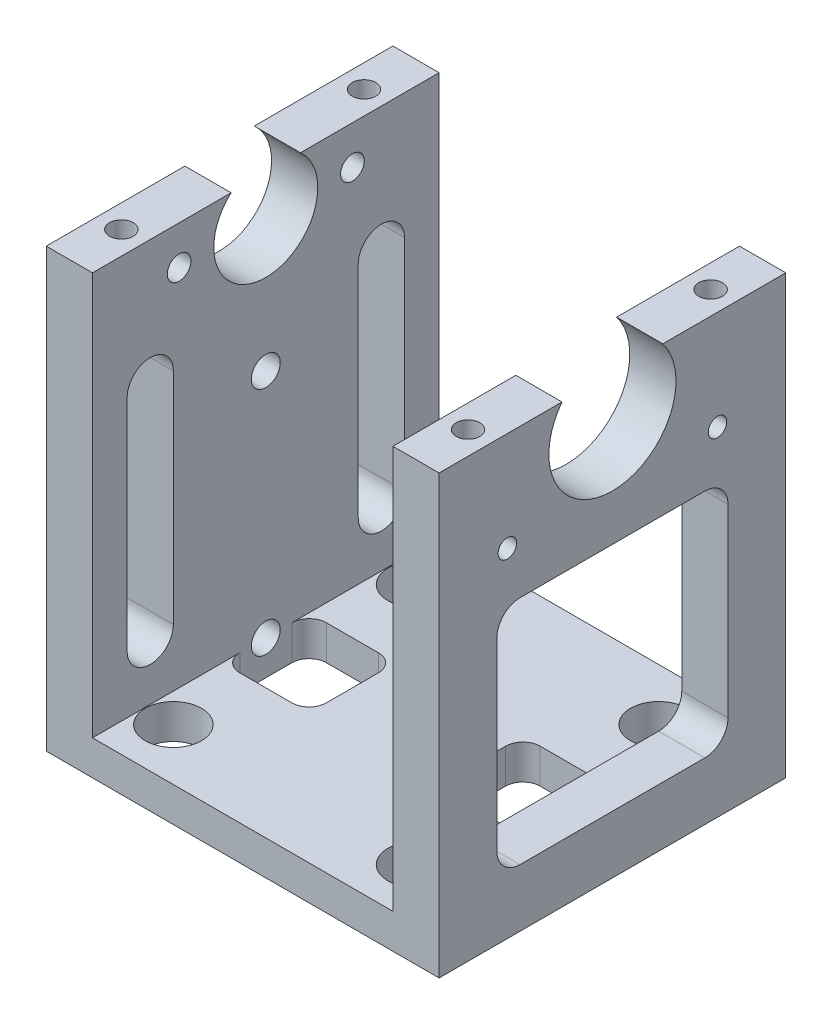
SolidWorks part; units mm, degrees
material "6061 合金"
ref_plane "前视基准面" through (0, 0, 0) normal (0, 0, 1) x (1, 0, 0)
ref_plane "上视基准面" through (0, 0, 0) normal (0, 1, 0) x (1, 0, 0)
ref_plane "右视基准面" through (0, 0, 0) normal (1, 0, 0) x (0, 0, -1)
sketch "草图1" plane through (0, 0, 0) normal (0, 0, 1) x (1, 0, 0)
  line L0 (0, 0) -> (34, 0)
  line L1 (34, 0) -> (34, 44.5)
  line L2 (0, 0) -> (0, 42)
  line L3 (30, 4) -> (30, 44.5)
  line L5 (4, 4) -> (4, 42)
  line L6 (0, 42) -> (4, 42)
  line L7 (30, 44.5) -> (34, 44.5)
  line L8 (30, 4) -> (30, 3)
  line L9 (30, 3) -> (4, 3)
  line L10 (4, 3) -> (4, 4)
  line L12 (4, 4) -> (30, 4) construction
  dimension "D1" = 34
  dimension "D2" = 44.5
  dimension "D3" = 42
  dimension "D4" = 4
  dimension "D5" = 1
extrude "凸台-拉伸1" add sketch "草图1" along normal mid plane 30
chamfer "倒角1" distance 10 angle 45 4 edges at (32, 44.5, -15) (32, 44.5, 15) (2, 42, -15) (2, 42, 15)
sketch "草图2" plane through (34, 0, 0) normal (1, 0, 0) x (0, 0, -1)
  line L0 (-5, 44.5) -> (5, 44.5) construction
  circle A0 centre (0, 34.5) radius 4.5
  dimension "D1" = 9
  dimension "D2" = 10
extrude "切除-拉伸1" cut sketch "草图2" against normal through all
sketch "草图3" plane through (34, 0, 0) normal (1, 0, 0) x (0, 0, -1)
  line L0 (-5, 44.5) -> (5, 44.5) construction
  line L1 (-10, 25) -> (10, 25)
  line L2 (-10, 25) -> (-10, 5)
  line L3 (-10, 5) -> (10, 5)
  line L4 (10, 25) -> (10, 5)
  line L5 (-10, 25) -> (10, 5) construction
  line L6 (-10, 5) -> (10, 25) construction
  point P0 (0, 15)
  dimension "D1" = 20
  dimension "D2" = 19.5
  dimension "D3" = 20
extrude "切除-拉伸2" cut sketch "草图3" against normal blind 10
fillet "圆角1" radius 2 4 edges at (32, 25, 10) (32, 25, -10) (32, 5, -10) (32, 5, 10)
sketch "草图4" plane through (0, 0, 0) normal (-1, 0, 0) x (0, 0, 1)
  line L0 (0, 0) -> (0, 42) construction
  line L1 (5, 42) -> (-5, 42) construction
  line L2 (15, 0) -> (-15, 0) construction
  line L3 (-4.5, 28) -> (4.5, 28)
  line L4 (-4.5, 28) -> (-4.5, 0)
  line L5 (-4.5, 0) -> (4.5, 0)
  line L6 (4.5, 28) -> (4.5, 0)
  dimension "D1" = 9
  dimension "D2" = 4.5
  dimension "D3" = 28
extrude "切除-拉伸3" cut sketch "草图4" against normal blind 1
fillet "圆角2" radius 2 2 edges at (0.5, 28, -4.5) (0.5, 28, 4.5)
sketch "草图5" plane through (34, 0, 0) normal (1, 0, 0) x (0, 0, -1)
  line L0 (-15, 34.5) -> (15, 34.5) construction
  line L1 (0, 44.5) -> (0, 29.6692) construction
  line L2 (-5, 44.5) -> (5, 44.5) construction
  line L3 (-3, 44.5) -> (-3, 29.6692) construction
  line L4 (3, 44.5) -> (3, 29.6692) construction
  line L5 (-3, 37.8541) -> (-15, 37.8541)
  line L6 (-3, 37.8541) -> (15, 37.8541)
  line L7 (15, 37.8541) -> (15, 44.5)
  line L8 (15, 44.5) -> (-15, 44.5)
  line L9 (-15, 44.5) -> (-15, 37.8541)
  circle A0 centre (0, 34.5) radius 4.5 construction
  point P0 (0, 45)
  point P17 (0, 34.5)
  point P21 (9.0933, 29.25)
  point P22 (-9.0933, 29.25)
  point P23 (0, 34.5)
  dimension "D1" = 10.5
  dimension "D2" = 3
  dimension "D3" = 3
hole_wizard "M2 螺纹孔2" positions "3D草图2" profile "草图7" tap size "M2" standard "GB"
sketch3d "3D草图2"
  point P0 (34, 29.25, 9.0933)
  point P3 (34, 29.25, -9.0933)
sketch "草图7" plane through (34, 29.25, 9.0933) normal (0, 1, 0) x (0, 0, -1)
  line L0 (0, 0) -> (0, 6.4807)
  line L1 (0, 6.4807) -> (0.8, 6)
  line L2 (0.8, 6) -> (0.8, 0)
  line L5 (0.8, 0) -> (0, 0)
  line L10 (0, 6.4807) -> (-0.8, 6) construction
  line L11 (0, -6.35) -> (0, 107.95) construction
  dimension "螺纹孔钻头直径" = 1.6
  dimension "螺纹孔钻头深度" = 6
  dimension "导头角度" = 118
cosmetic thread "孔螺蚊线2" parameters "D1"=4, "D2"=2
cosmetic thread "孔螺蚊线3" parameters "D1"=4, "D2"=2
extrude "切除-拉伸4" cut sketch "草图5" against normal through all
sketch "草图9" plane through (0, 0, 0) normal (-1, 0, 0) x (0, 0, 1)
  line L0 (15, 32) -> (15, 37.8541)
  line L1 (15, 37.8541) -> (9.1459, 37.8541)
  line L2 (9.1459, 37.8541) -> (15, 32)
  line L3 (-15, 32) -> (-15, 37.8541)
  line L4 (-15, 37.8541) -> (-9.1459, 37.8541)
  line M1 (15, 32) -> (9.1459, 37.8541)
  line M5 (-9.1459, 37.8541) -> (-15, 32)
extrude "凸台-拉伸2" add sketch "草图9" against normal blind 4 contours L0 L1 M1 | L4 L3 M5
sketch "草图10" plane through (34, 0, 0) normal (1, 0, 0) x (0, 0, -1)
  line L0 (11.6459, 37.8541) -> (15, 37.8541)
  line L1 (15, 37.8541) -> (3, 37.8541) construction
  line L2 (15, 3) -> (15, 37.8541) construction
  line L3 (15, 37.8541) -> (15, 34.5)
  line L4 (15, 34.5) -> (11.6459, 37.8541)
  line L5 (-15, 34.5) -> (-15, 37.8541)
  line L6 (-15, 37.8541) -> (-11.6459, 37.8541)
  line L7 (-11.6459, 37.8541) -> (-15, 34.5)
extrude "凸台-拉伸3" add sketch "草图10" against normal blind 4
sketch "草图11" plane through (0, 0, 0) normal (-1, 0, 0) x (0, 0, 1)
  line L0 (-10, 27) -> (-10, 8) construction
  line L1 (-4.5, 0) -> (-15, 0) construction
  line L2 (-8, 27) -> (-8, 8)
  line L3 (-12, 27) -> (-12, 8)
  line L5 (0, 0) -> (0, 37.2192) construction
  line L6 (10, 27) -> (10, 8) construction
  line L7 (8, 27) -> (8, 8)
  line L8 (12, 27) -> (12, 8)
  arc A0 (-8, 27) -> (-12, 27) centre (-10, 27) ccw
  arc A1 (-12, 8) -> (-8, 8) centre (-10, 8) ccw
  arc A2 (8, 27) -> (12, 27) centre (10, 27) cw
  arc A3 (12, 8) -> (8, 8) centre (10, 8) cw
  point P4 (-10, 17.5)
  point P14 (10, 17.5)
  dimension "D1" = 8
  dimension "D2" = 4
  dimension "D3" = 10
  dimension "D4" = 19
extrude "切除-拉伸5" cut sketch "草图11" against normal blind 4
sketch "草图12" plane through (0, 0, 0) normal (0, -1, 0) x (1, 0, 0)
  line L0 (0, 0) -> (4, 0) construction
  line L1 (4, 3.75) -> (11.5, 3.75)
  line L2 (4, 3.75) -> (4, -3.75)
  line L3 (4, -3.75) -> (11.5, -3.75)
  line L4 (11.5, 3.75) -> (11.5, -3.75)
  line L5 (4, 3.75) -> (11.5, -3.75) construction
  line L6 (4, -3.75) -> (11.5, 3.75) construction
  line L7 (0, -4.5) -> (0, -15) construction
  point P0 (7.75, 0)
  dimension "D1" = 7.5
  dimension "D2" = 7.75
extrude "切除-拉伸6" cut sketch "草图12" against normal blind 4
fillet "圆角3" radius 1.5 4 edges at (4, 1.5, -3.75) (11.5, 1.5, -3.75) (11.5, 1.5, 3.75) (4, 1.5, 3.75)
sketch "草图13" plane through (1, 0, 0) normal (-1, 0, 0) x (0, 0, 1)
  line L0 (2.5, 28) -> (-2.5, 28) construction
  point P0 (0, 23)
  point P3 (0, 3)
  dimension "D1" = 5
  dimension "D2" = 20
hole_wizard "M3 螺纹孔1" positions "3D草图3" profile "草图14" tap size "M3" standard "GB"
sketch3d "3D草图3"
  point P0 (1, 23, 0)
  point P3 (1, 3, 0)
sketch "草图14" plane through (1, 23, 0) normal (0, 1, 0) x (0, 0, 1)
  line L0 (0, 0) -> (0, 9.2511)
  line L1 (0, 9.2511) -> (1.25, 8.5)
  line L2 (1.25, 8.5) -> (1.25, 0)
  line L5 (1.25, 0) -> (0, 0)
  line L10 (0, 9.2511) -> (-1.25, 8.5) construction
  line L11 (0, -6.35) -> (0, 107.95) construction
  dimension "螺纹孔钻头直径" = 2.5
  dimension "螺纹孔钻头深度" = 8.5
  dimension "导头角度" = 118
cosmetic thread "孔螺蚊线4" parameters "D1"=2.5, "D2"=3
cosmetic thread "孔螺蚊线5" parameters "D1"=2.5, "D2"=3
sketch "草图15" plane through (0, 0, 0) normal (0, -1, 0) x (1, 0, 0)
  line L0 (30, 0) -> (34, 0) construction
  line L1 (6.5, -10.5) -> (27.5, -10.5) construction
  line L2 (6.5, -10.5) -> (6.5, 10.5) construction
  line L3 (6.5, 10.5) -> (27.5, 10.5) construction
  line L4 (27.5, -10.5) -> (27.5, 10.5) construction
  line L5 (6.5, -10.5) -> (27.5, 10.5) construction
  line L6 (6.5, 10.5) -> (27.5, -10.5) construction
  point P0 (17, 0)
  dimension "D1" = 21
sketch "草图17" plane through (0, 0, 0) normal (0, -1, 0) x (1, 0, 0)
  circle A0 centre (17, 0) radius 4.875
  dimension "D1" = 9.75
extrude "切除-拉伸8" cut sketch "草图17" against normal blind 1
ref_plane "基准面1" through (17, 0, 0) normal (-1, 0, 0) x (0, 0, 1)
mirror "镜向2" about plane through (17, 0, 0) normal (-1, 0, 0) of "切除-拉伸6"
fillet "圆角4" radius 1.5 4 edges at (22.5, 1.5, -3.75) (30, 1.5, -3.75) (30, 1.5, 3.75) (22.5, 1.5, 3.75)
sketch "草图19" plane through (0, 37.8541, 0) normal (0, 1, 0) x (1, 0, 0)
  point P0 (32, -10.5)
  point P1 (32, 10.5)
hole_wizard "M2.5 螺纹孔1" positions "3D草图5" profile "草图20" tap size "M2.5" standard "GB"
sketch3d "3D草图5"
  point P0 (32, 37.8541, 10.5)
  point P3 (32, 37.8541, -10.5)
sketch "草图20" plane through (32, 37.8541, 10.5) normal (1, 0, 0) x (0, 0, 1)
  line L0 (0, 0) -> (0, 6.8659)
  line L1 (0, 6.8659) -> (1.025, 6.25)
  line L2 (1.025, 6.25) -> (1.025, 0)
  line L5 (1.025, 0) -> (0, 0)
  line L10 (0, 6.8659) -> (-1.025, 6.25) construction
  line L11 (0, -6.35) -> (0, 107.95) construction
  dimension "螺纹孔钻头直径" = 2.05
  dimension "螺纹孔钻头深度" = 6.25
  dimension "导头角度" = 118
cosmetic thread "孔螺蚊线10" parameters "D1"=4, "D2"=2.5
cosmetic thread "孔螺蚊线11" parameters "D1"=4, "D2"=2.5
mirror "镜向3" about plane through (17, 0, 0) normal (-1, 0, 0) of "M2.5 螺纹孔1"
sketch "草图21" plane through (0, 0, 0) normal (-1, 0, 0) x (0, 0, 1)
  point P0 (7.5, 34.5)
  point P1 (-7.5, 34.5)
hole_wizard "M2.5 螺纹孔2" positions "3D草图7" profile "草图23" tap size "M2.5" standard "GB"
sketch3d "3D草图7"
  point P0 (0, 34.5, 7.5)
  point P3 (0, 34.5, -7.5)
sketch "草图23" plane through (0, 34.5, 7.5) normal (0, 1, 0) x (0, 0, 1)
  line L0 (0, 0) -> (0, 6.8659)
  line L1 (0, 6.8659) -> (1.025, 6.25)
  line L2 (1.025, 6.25) -> (1.025, 0)
  line L5 (1.025, 0) -> (0, 0)
  line L10 (0, 6.8659) -> (-1.025, 6.25) construction
  line L11 (0, -6.35) -> (0, 107.95) construction
  dimension "螺纹孔钻头直径" = 2.05
  dimension "螺纹孔钻头深度" = 6.25
  dimension "导头角度" = 118
cosmetic thread "孔螺蚊线12" parameters "D1"=4, "D2"=2.5
cosmetic thread "孔螺蚊线13" parameters "D1"=4, "D2"=2.5
sketch "草图24" plane through (0, 0, 0) normal (0, -1, 0) x (1, 0, 0)
  circle A0 centre (6.5, 10.5) radius 2.435
  circle A1 centre (27.5, 10.5) radius 2.435
  circle A2 centre (6.5, -10.5) radius 2.435
  circle A3 centre (27.5, -10.5) radius 2.435
  dimension "D1" = 4.87
  dimension "D2" = 4.87
  dimension "D3" = 4.87
  dimension "D4" = 4.87
extrude "切除-拉伸9" cut sketch "草图24" against normal blind 10
sketch "草图25" plane through (34, 0, 0) normal (1, 0, 0) x (0, 0, -1)
  circle A0 centre (0, 34.5) radius 5.5
  dimension "D1" = 11
extrude "切除-拉伸10" cut sketch "草图25" against normal blind 10
